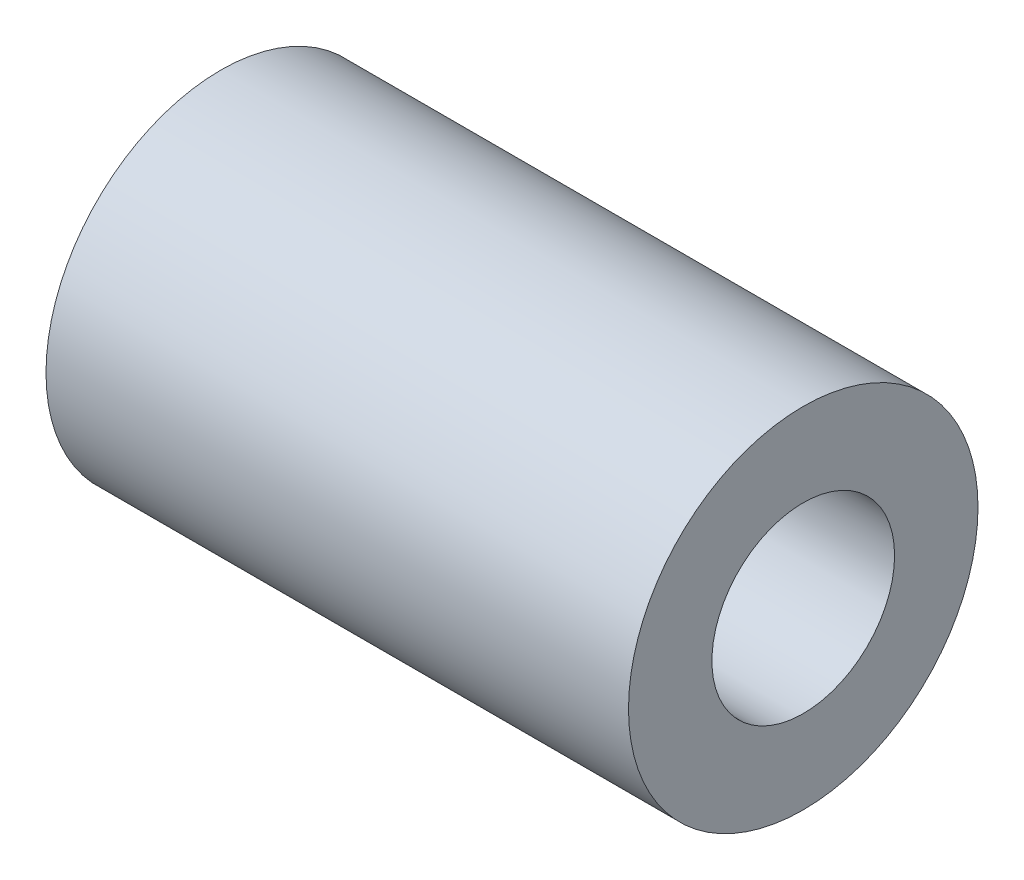
SolidWorks part; units mm, degrees
ref_plane "Front Plane" through (0, 0, 0) normal (0, 0, 1) x (1, 0, 0)
ref_plane "Top Plane" through (0, 0, 0) normal (0, 1, 0) x (1, 0, 0)
ref_plane "Right Plane" through (0, 0, 0) normal (1, 0, 0) x (0, 0, -1)
sketch "Sketch1" plane through (0, 0, 0) normal (1, 0, 0) x (0, 0, -1)
  circle A0 centre (0, 0) radius 4.7625
  circle A1 centre (0, 0) radius 2.4892
extrude "Boss-Extrude1" add sketch "Sketch1" along normal blind 15.875
